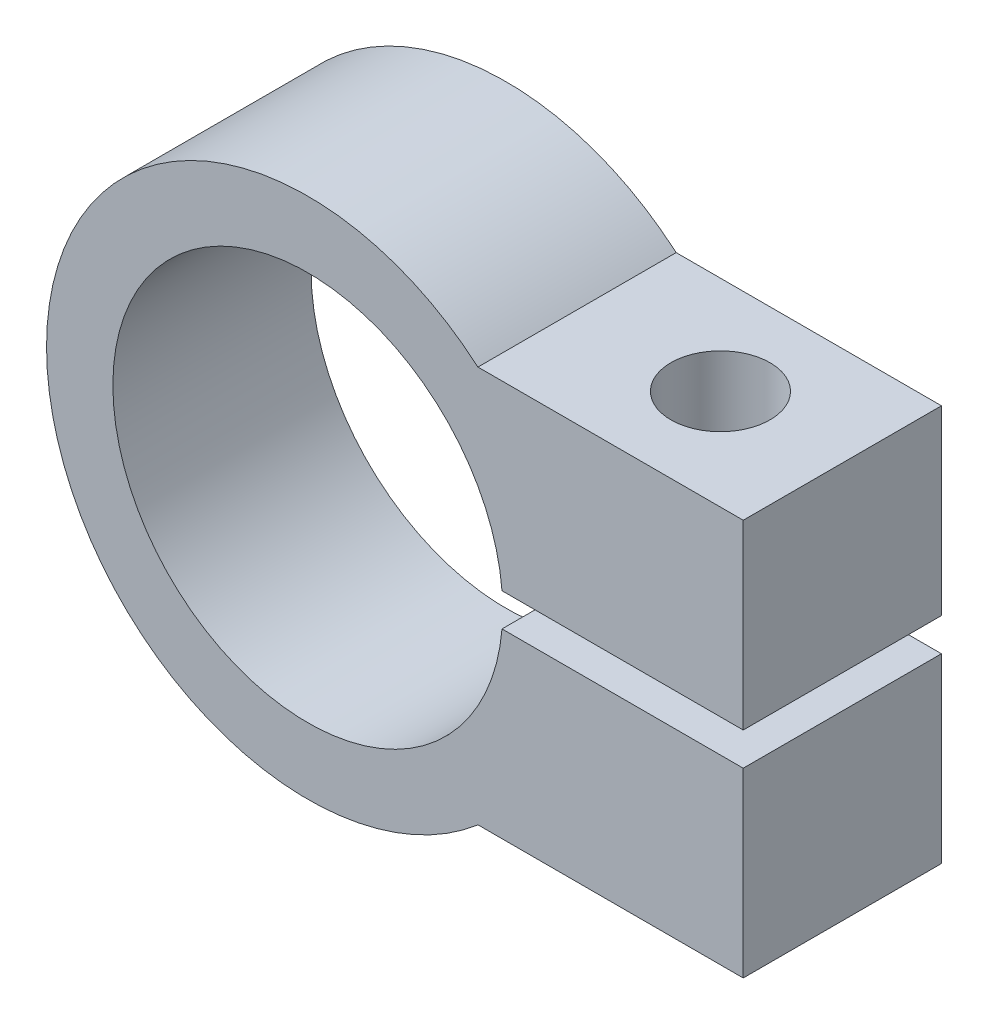
SolidWorks part; units mm, degrees
ref_plane "Front Plane" through (0, 0, 0) normal (0, 0, 1) x (1, 0, 0)
ref_plane "Top Plane" through (0, 0, 0) normal (0, 1, 0) x (1, 0, 0)
ref_plane "Right Plane" through (0, 0, 0) normal (1, 0, 0) x (0, 0, -1)
sketch "Sketch1" plane through (0, 0, 0) normal (0, 0, 1) x (1, 0, 0)
  line L0 (-40.8525, 55.2532) -> (-32.8228, 55.2532)
  line L2 (-32.8228, 55.2532) -> (-32.8228, 49.7532)
  line L3 (-32.8228, 49.7532) -> (-40.1242, 49.7532)
  line L4 (-46.003, 49.2532) -> (-25.3566, 49.2532) construction
  line L5 (-32.8228, 48.7532) -> (-40.1242, 48.7532)
  line L6 (-40.8525, 43.2532) -> (-32.8228, 43.2532)
  line L7 (-32.8228, 43.2532) -> (-32.8228, 48.7532)
  arc A0 (-40.8525, 55.2532) -> (-40.8525, 43.2532) centre (-46.003, 49.2532) ccw
  arc A2 (-38.1113, 48.7532) -> (-38.1113, 49.7532) centre (-46.003, 49.2532) ccw
  circle A3 centre (-46.003, 49.2532) radius 5.9
  dimension "D2" = 1
extrude "Boss-Extrude1" add sketch "Sketch1" along normal blind 6 contours A3 L3 L2 L0 A0 L6 L7 L5
sketch "Sketch2" plane through (0, 55.2532, 0) normal (0, 1, 0) x (1, 0, 0)
  circle A0 centre (-36.5475, -2.9648) radius 1.5
extrude "Cut-Extrude1" cut sketch "Sketch2" against normal blind 14
